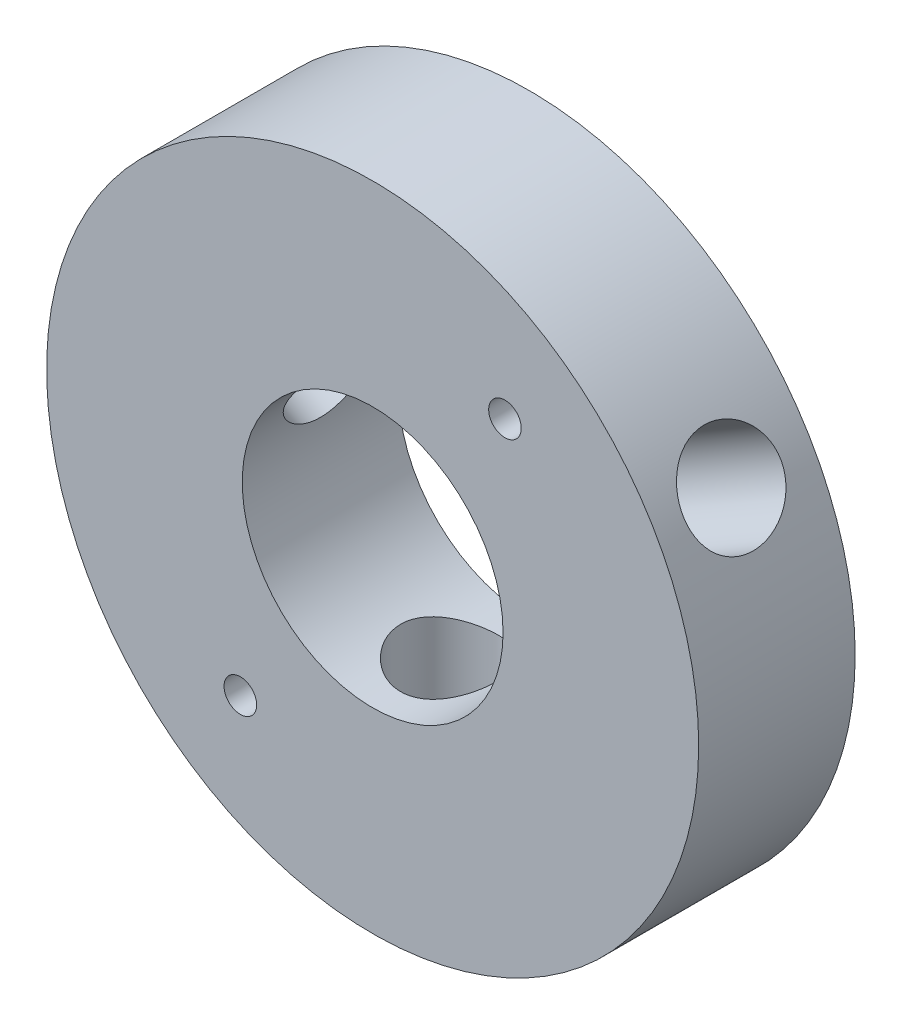
SolidWorks part; units mm, degrees
ref_plane "Front Plane" through (0, 0, 0) normal (0, 0, 1) x (1, 0, 0)
ref_plane "Top Plane" through (0, 0, 0) normal (0, 1, 0) x (1, 0, 0)
ref_plane "Right Plane" through (0, 0, 0) normal (1, 0, 0) x (0, 0, -1)
sketch "Sketch1" plane through (0, 0, 0) normal (0, 0, 1) x (1, 0, 0)
  circle A0 centre (0, 0) radius 15.875
  dimension "D1" = 31.75
extrude "Boss-Extrude1" add sketch "Sketch1" along normal blind 7.62
sketch "Sketch2" plane through (0, 0, 7.62) normal (0, 0, 1) x (1, 0, 0)
  circle A0 centre (0, 0) radius 6.35
  dimension "D1" = 12.7
extrude "Cut-Extrude1" cut sketch "Sketch2" against normal through all
ref_plane "Plane1" through (0, 0, 3.81) normal (0, 0, 1) x (1, 0, 0)
sketch "Sketch11" plane through (0, 0, 3.81) normal (0, 0, 1) x (1, 0, 0)
  point P0 (-31.3984, 15.2938)
  point P1 (31.3893, 15.3123)
  point P3 (0, -34.925)
sketch "Sketch33" plane through (0, 0, 7.62) normal (0, 0, 1) x (1, 0, 0)
  line L0 (-7.6406, 13.9153) -> (7.6406, -13.9153)
  circle A0 centre (0, 0) radius 15.875 construction
sketch "Sketch34" plane through (0, 0, 7.62) normal (0, 0, 1) x (1, 0, 0)
  line L0 (7.6406, -13.9153) -> (3.048, -5.5707)
  line L1 (-7.6406, 13.9153) -> (-10.7006, 19.4883)
  circle A0 centre (0, 0) radius 6.35 construction
  point P8 (5.3443, -9.743)
  point P9 (-9.1706, 16.7018)
ref_plane "Plane2" through (0, -15.875, 0) normal (0, -1, 0) x (-1, 0, 0)
hole_wizard "3/16 (0.1875) Diameter Hole1" positions "Sketch35" profile "Sketch36" hole size "3/16" standard "ANSI Inch"
sketch "Sketch35" plane through (0, -15.875, 0) normal (0, -1, 0) x (-1, 0, 0)
  point P0 (0, -3.8772)
sketch "Sketch36" plane through (0, -15.875, 3.8772) normal (1, 0, 0) x (0, 0, -1)
  line L0 (0, 0) -> (0, 20.4808)
  line L1 (0, 20.4808) -> (2.3812, 19.05)
  line L2 (2.3812, 19.05) -> (2.3812, 0)
  line L5 (2.3812, 0) -> (0, 0)
  line L10 (0, 20.4808) -> (-2.3813, 19.05) construction
  line L11 (0, -6.35) -> (0, 107.95) construction
  dimension "Hole Dia." = 4.7625
  dimension "Hole Depth" = 19.05
  dimension "Drill Angle" = 118
pattern_circular "CirPattern1" count 3 every 120 about axis through (0, 0, 7.62) along (0, 0, -1) of "3/16 (0.1875) Diameter Hole1"
sketch "Sketch37" plane through (0, 0, 0) normal (0, 0, -1) x (-1, 0, 0)
  line L0 (0, 0) -> (-12.587, -13.4418)
  dimension "D2" = 18.415
sketch "Sketch38" plane through (0, 0, 0) normal (0, 0, -1) x (-1, 0, 0)
  line L0 (0, 0) -> (-6.4423, 9.0545)
  dimension "D1" = 11.1125
hole_wizard "1/16 (0.0625) Diameter Hole1" positions "Sketch39" profile "Sketch40" hole size "1/16" standard "ANSI Inch" end condition through all
sketch "Sketch39" plane through (0, 0, 0) normal (0, 0, -1) x (-1, 0, 0)
  point P0 (-6.4423, 9.0545)
sketch "Sketch40" plane through (6.4423, 9.0545, 0) normal (1, 0, 0) x (0, 1, 0)
  line L0 (0, 0) -> (0, 7.62)
  line L1 (0, 7.62) -> (0.7937, 7.62)
  line L2 (0.7937, 7.62) -> (0.7937, 0.5328)
  line L3 (0.7937, 0.5328) -> (1.4287, 0)
  line L5 (1.4287, 0) -> (0, 0)
  line L6 (-0.7937, 0.5328) -> (-1.4287, 0) construction
  line L11 (0, -6.35) -> (0, 107.95) construction
  dimension "Thru Hole Dia." = 1.5875
  dimension "Thru Hole Depth" = 7.62
  dimension "Near C'Sink Dia." = 2.8575
  dimension "Near C'Sink Angle" = 100
pattern_circular "CirPattern2" count 2 every 180 about axis through (0, 0, 0) along (0, 0, 1) of "1/16 (0.0625) Diameter Hole1"
